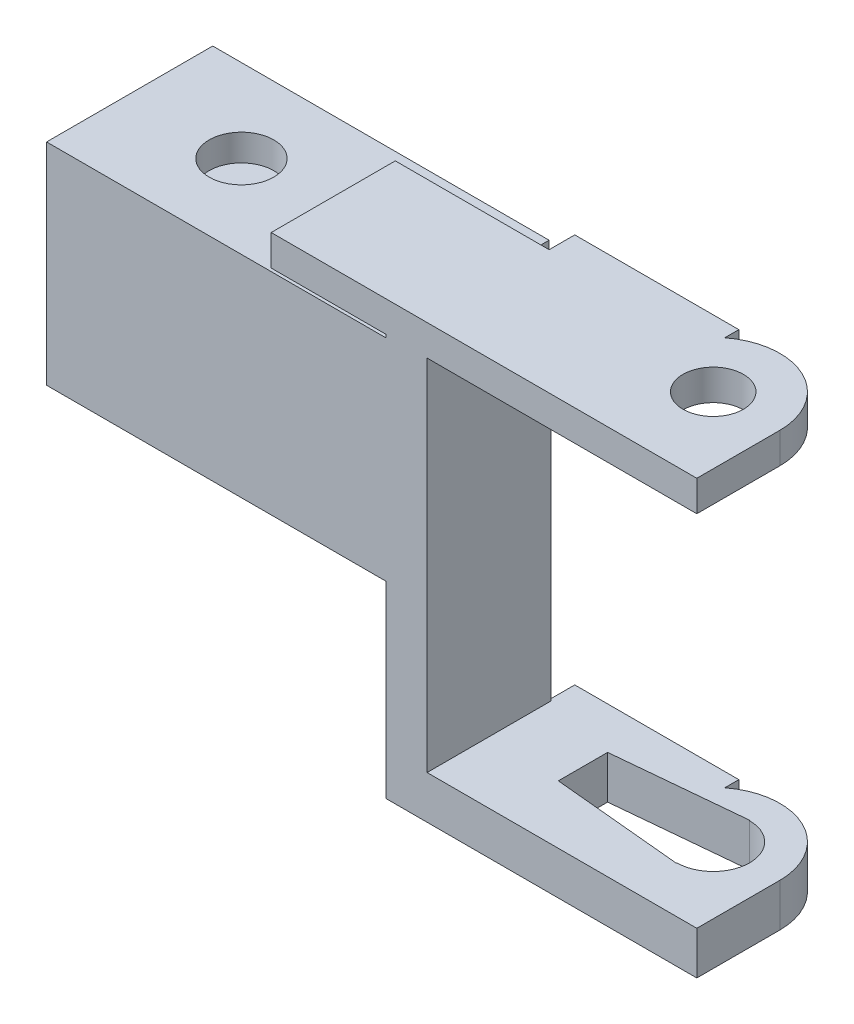
SolidWorks part; units mm, degrees
material "ABS"
ref_plane "Front Plane" through (0, 0, 0) normal (0, 0, 1) x (1, 0, 0)
ref_plane "Top Plane" through (0, 0, 0) normal (0, 1, 0) x (1, 0, 0)
ref_plane "Right Plane" through (0, 0, 0) normal (1, 0, 0) x (0, 0, -1)
sketch "Sketch1" plane through (0, 0, 0) normal (0, 1, 0) x (1, 0, 0)
  line L1 (35.1, -8.1) -> (67.9, -8.1)
  line L2 (35.1, -8.1) -> (35.1, 8.1)
  line L3 (35.1, 8.1) -> (67.9, 8.1)
  line L4 (67.9, -8.1) -> (67.9, 8.1)
extrude "Boss-Extrude1" add sketch "Sketch1" along normal mid plane 20.55 from offset 17.075
sketch "Sketch2" plane through (0, 0, 0) normal (0, 1, 0) x (1, 0, 0)
  line L0 (35.1, -8.1) -> (67.9, -8.1) construction
  line L1 (57, -8.1) -> (88, -8.1)
  line L2 (57, -8.1) -> (57, 4)
  line L3 (57, 4) -> (88, 4)
  line L4 (88, -8.1) -> (88, 4)
extrude "Boss-Extrude2" add sketch "Sketch2" along normal mid plane 3 from offset 5
sketch "Sketch3" plane through (0, 0, 0) normal (0, 1, 0) x (1, 0, 0)
  line L0 (57, -8.1) -> (88, -8.1) construction
  line L1 (72, -8.1) -> (88, -8.1)
  line L2 (72, -8.1) -> (72, 6.5)
  line L3 (72, 6.5) -> (88, 6.5)
  line L4 (88, -8.1) -> (88, 6.5)
extrude "Boss-Extrude3" add sketch "Sketch3" along normal mid plane 3 from offset 5
sketch "Sketch4" plane through (0, 0, 0) normal (0, 1, 0) x (1, 0, 0)
  line L1 (88, -8.1) -> (98.5, -8.1)
  line L2 (88, -8.1) -> (88, 0)
  line L3 (88, 0) -> (98.5, 0)
  line L4 (98.5, -8.1) -> (98.5, 0)
extrude "Boss-Extrude4" add sketch "Sketch4" along normal mid plane 3 from offset 5
sketch "Sketch5" plane through (0, 0, 0) normal (0, 1, 0) x (1, 0, 0)
  circle A0 centre (92, 0) radius 6.5
extrude "Boss-Extrude5" add sketch "Sketch5" along normal mid plane 3 from offset 5
sketch "Sketch6" plane through (0, 0, 0) normal (0, 1, 0) x (1, 0, 0)
  circle A0 centre (92, 0) radius 2.95
extrude "Cut-Extrude1" cut sketch "Sketch6" against normal mid plane 3 from offset 5
sketch "Sketch7" plane through (0, 0, 0) normal (1, 0, 0) x (0, 0, -1)
  line L1 (-8.1, -45.7) -> (4, -45.7)
  line L2 (-8.1, -45.7) -> (-8.1, -3.5)
  line L3 (-8.1, -3.5) -> (4, -3.5)
  line L4 (4, -45.7) -> (4, -3.5)
extrude "Boss-Extrude6" add sketch "Sketch7" along normal mid plane 4 from offset 70.2
sketch "Sketch8" plane through (0, 0, 0) normal (1, 0, 0) x (0, 0, -1)
  line L0 (4, -45.7) -> (4, -6.5) construction
  line L1 (-8.1, -27.35) -> (4, -27.35)
  line L2 (-8.1, -27.35) -> (-8.1, -6.8)
  line L3 (-8.1, -6.8) -> (4, -6.8)
  line L4 (4, -27.35) -> (4, -6.8)
extrude "Boss-Extrude7" add sketch "Sketch8" along normal mid plane 2.3 from offset 68.05
sketch "Sketch9" plane through (0, 0, 0) normal (0, 1, 0) x (1, 0, 0)
  line L0 (57, -8.1) -> (98.5, -8.1) construction
  line L1 (68.2, -8.1) -> (88, -8.1)
  line L2 (68.2, -8.1) -> (68.2, 4)
  line L3 (68.2, 4) -> (88, 4)
  line L4 (88, -8.1) -> (88, 4)
extrude "Boss-Extrude8" add sketch "Sketch9" along normal mid plane 4.2 from offset 43.6
sketch "Sketch10" plane through (0, 0, 0) normal (0, 1, 0) x (1, 0, 0)
  line L0 (57, -8.1) -> (98.5, -8.1) construction
  line L1 (72, -8.1) -> (88, -8.1)
  line L2 (72, -8.1) -> (72, 6.5)
  line L3 (72, 6.5) -> (88, 6.5)
  line L4 (88, -8.1) -> (88, 6.5)
extrude "Boss-Extrude9" add sketch "Sketch10" along normal mid plane 4.2 from offset 43.6
sketch "Sketch11" plane through (0, 0, 0) normal (0, 1, 0) x (1, 0, 0)
  line L0 (57, -8.1) -> (98.5, -8.1) construction
  line L1 (88, -8.1) -> (98.5, -8.1)
  line L2 (88, -8.1) -> (88, 0)
  line L3 (88, 0) -> (98.5, 0)
  line L4 (98.5, -8.1) -> (98.5, 0)
extrude "Boss-Extrude10" add sketch "Sketch11" along normal mid plane 4.2 from offset 43.6
sketch "Sketch12" plane through (0, 0, 0) normal (0, 1, 0) x (1, 0, 0)
  circle A0 centre (92, 0) radius 6.5
extrude "Boss-Extrude11" add sketch "Sketch12" along normal mid plane 4.2 from offset 43.6
sketch "Sketch13" plane through (0, 0, 0) normal (0, 1, 0) x (1, 0, 0)
  circle A0 centre (92, 0) radius 3.55
extrude "Cut-Extrude2" cut sketch "Sketch13" against normal mid plane 4.2 from offset 43.6
sketch "Sketch14" plane through (0, 0, 0) normal (0, 1, 0) x (1, 0, 0)
  line L0 (92, 3.6038) -> (79.3, 2.4033)
  line L1 (79.3, 2.4033) -> (79.3, -2.4033)
  line L2 (79.3, -2.4033) -> (92, -3.6038)
  line L3 (92, -3.6038) -> (92, 3.6038)
extrude "Cut-Extrude3" cut sketch "Sketch14" against normal mid plane 4.2 from offset 43.6
sketch "Sketch15" plane through (0, 0, 0) normal (0, 1, 0) x (1, 0, 0)
  line L1 (39.9, -6.5) -> (63.1, -6.5)
  line L2 (39.9, -6.5) -> (39.9, 6.5)
  line L3 (39.9, 6.5) -> (63.1, 6.5)
  line L4 (63.1, -6.5) -> (63.1, 6.5)
extrude "Cut-Extrude4" cut sketch "Sketch15" against normal mid plane 17.25 from offset 18.725
sketch "Sketch16" plane through (0, 0, 0) normal (0, 1, 0) x (1, 0, 0)
  circle A0 centre (65.25, 0) radius 1
extrude "Cut-Extrude5" cut sketch "Sketch16" against normal mid plane 6 from offset 24.35
sketch "Sketch17" plane through (0, 0, 0) normal (0, 1, 0) x (1, 0, 0)
  circle A0 centre (37.75, 0) radius 1
extrude "Cut-Extrude6" cut sketch "Sketch17" against normal mid plane 6 from offset 24.35
sketch "Sketch18" plane through (0, 0, 0) normal (0, 1, 0) x (1, 0, 0)
  circle A0 centre (46, 0) radius 3.15
extrude "Cut-Extrude7" cut sketch "Sketch18" against normal mid plane 2.6 from offset 8.1
sketch "Sketch19" plane through (0, 0, 0) normal (1, 0, 0) x (0, 0, -1)
  line L1 (-2.2, -16.1) -> (2.2, -16.1)
  line L2 (-2.2, -16.1) -> (-2.2, -10.1)
  line L3 (-2.2, -10.1) -> (2.2, -10.1)
  line L4 (2.2, -16.1) -> (2.2, -10.1)
extrude "Cut-Extrude8" cut sketch "Sketch19" against normal mid plane 4.8 from offset 37.5
